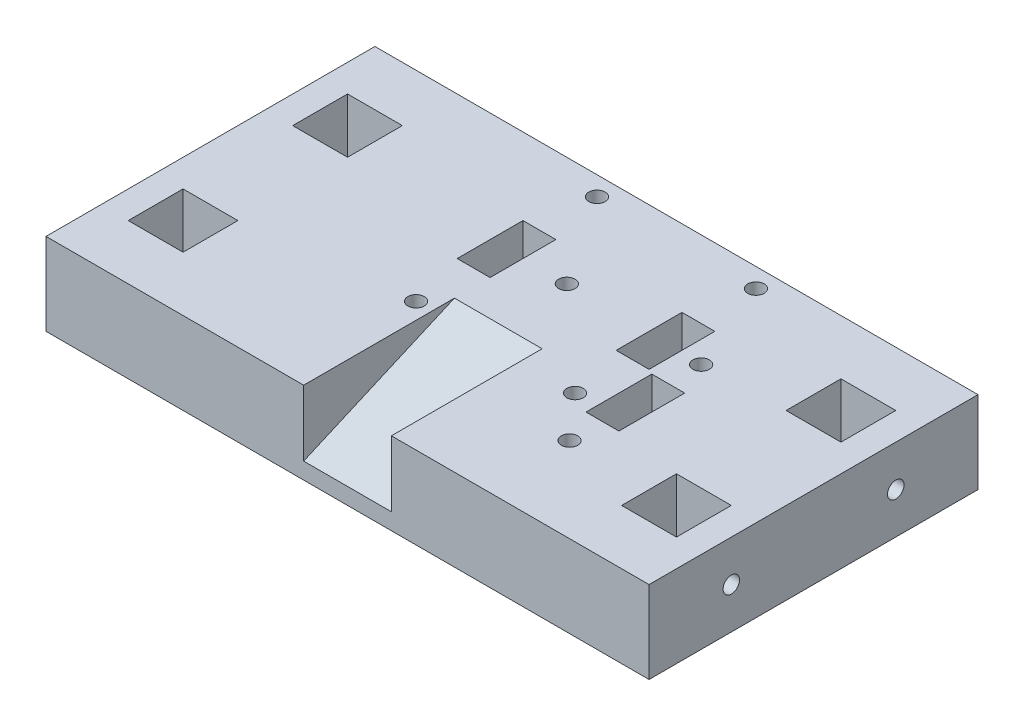
SolidWorks part; units mm, degrees
ref_plane "Alzado" through (0, 0, 0) normal (0, 0, 1) x (1, 0, 0)
ref_plane "Planta" through (0, 0, 0) normal (0, 1, 0) x (1, 0, 0)
ref_plane "Vista lateral" through (0, 0, 0) normal (1, 0, 0) x (0, 0, -1)
sketch "Croquis1" plane through (0, 0, 0) normal (0, 1, 0) x (1, 0, 0)
  line L0 (-50, 0) -> (55, 0) construction
  line L1 (0, 7.75) -> (-6.7117, 3.875)
  line L2 (-6.7117, 3.875) -> (-6.7117, -3.875)
  line L3 (-6.7117, -3.875) -> (0, -7.75)
  line L4 (0, -7.75) -> (6.7117, -3.875)
  line L5 (6.7117, -3.875) -> (6.7117, 3.875)
  line L6 (6.7117, 3.875) -> (0, 7.75)
  line L7 (-50, 20) -> (50, 20) construction
  line L8 (-50, -40) -> (50, -40) construction
  line L9 (-50, 10) -> (50, 10) construction
  line L10 (-50, 20) -> (-40, 20)
  line L11 (-50, 20) -> (-50, -40)
  line L12 (-50, -40) -> (-40, -40)
  line L13 (-40, 20) -> (-40, -40)
  line L14 (50, 20) -> (40, 20)
  line L15 (50, 20) -> (50, -40)
  line L16 (50, -40) -> (40, -40)
  line L17 (40, 20) -> (40, -40)
  line L18 (-40, 20) -> (40, 20)
  line L19 (-40, 20) -> (-40, -40)
  line L20 (-40, -40) -> (40, -40)
  line L21 (40, 20) -> (40, -40)
  line L22 (-50, -20) -> (50, -20) construction
  line L23 (-50, -30) -> (50, -30) construction
  line L24 (-14, 12.5) -> (21, 12.5) construction
  line L25 (-50, 10) -> (-40, 10)
  line L26 (-50, 10) -> (-50, 0)
  line L27 (-50, 0) -> (-40, 0)
  line L28 (-40, 10) -> (-40, 0)
  line L29 (50, 10) -> (40, 10)
  line L30 (50, 10) -> (50, 0)
  line L31 (50, 0) -> (40, 0)
  line L32 (40, 10) -> (40, 0)
  line L33 (50, -20) -> (40, -20)
  line L34 (50, -20) -> (50, -30)
  line L35 (50, -30) -> (40, -30)
  line L36 (40, -20) -> (40, -30)
  line L37 (-50, -20) -> (-40, -20)
  line L38 (-50, -20) -> (-50, -30)
  line L39 (-50, -30) -> (-40, -30)
  line L40 (-40, -20) -> (-40, -30)
  line L41 (-50, 20) -> (-55, 20)
  line L42 (-50, 20) -> (-50, -40)
  line L43 (-50, -40) -> (-55, -40)
  line L44 (-55, 20) -> (-55, -40)
  line L45 (50, 20) -> (55, 20)
  line L46 (50, 20) -> (50, -40)
  line L47 (50, -40) -> (55, -40)
  line L48 (55, 20) -> (55, -40)
  line L49 (-14, -12.5) -> (21, -12.5) construction
  line L50 (-11, 12.5) -> (-11, -12.5) construction
  line L51 (-14, 12.5) -> (-8, 12.5)
  line L52 (-14, 12.5) -> (-14, -12.5)
  line L53 (-14, -12.5) -> (-8, -12.5)
  line L54 (-8, 12.5) -> (-8, -12.5)
  line L55 (21, 12.5) -> (15, 12.5)
  line L56 (21, 12.5) -> (21, -12.5)
  line L57 (21, -12.5) -> (15, -12.5)
  line L58 (15, 12.5) -> (15, -12.5)
  line L59 (-14, 6) -> (-8, 6)
  line L60 (-14, 6) -> (-14, -6)
  line L61 (-14, -6) -> (-8, -6)
  line L62 (-8, 6) -> (-8, -6)
  line L63 (15, 6) -> (21, 6)
  line L64 (15, 6) -> (15, -6)
  line L65 (15, -6) -> (21, -6)
  line L66 (21, 6) -> (21, -6)
  line L67 (18, 12.5) -> (18, -12.5) construction
  circle A0 centre (0, 0) radius 7.75 construction
  circle A1 centre (-11, 16.5) radius 1.5
  circle A2 centre (18, 16.5) radius 1.5
  circle A3 centre (-11, -16.5) radius 1.5
  circle A4 centre (18, -16.5) radius 1.5
  dimension "D1" = 15.5
  dimension "D24" = 3
  dimension "D25" = 3
  dimension "D26" = 3
  dimension "D27" = 3
  dimension "D2" = 100
  dimension "D3" = 10
  dimension "D4" = 10
  dimension "D5" = 20
  dimension "D6" = 50
  dimension "D7" = 60
  dimension "D8" = 10
  dimension "D9" = 20
  dimension "D10" = 10
  dimension "D11" = 5
  dimension "D12" = 5
  dimension "D13" = 40
  dimension "D14" = 6
  dimension "D15" = 6
  dimension "D16" = 25
  dimension "D17" = 12.5
  dimension "D18" = 8
  dimension "D19" = 15
  dimension "D20" = 12
  dimension "D21" = 12
  dimension "D22" = 6.5
  dimension "D23" = 6.5
  dimension "D28" = 4
  dimension "D29" = 4
  dimension "D30" = 4
  dimension "D31" = 4
  dimension "D32" = 3
  dimension "D33" = 3
  dimension "D34" = 3
  dimension "D35" = 3
extrude "Saliente-Extruir1" add sketch "Croquis1" along normal blind 15 contours L13 L19 L20 L17 L21 L18 A4 A3 A2 A1 L58 L55 L56 L57 L6 L5 L4 L3 L2 L1 L51 L54 L53 L52 | L11 L37 L13 L27 | L39 L11 L12 L13 | L41 L44 L43 L11 | L11 L25 L13 L10 | L29 L15 L14 L17 | L48 L45 L15 L47 | L33 L15 L31 L17 | L15 L35 L17 L16 | L52 L59 L54 L51 | L61 L52 L53 L54 | L58 L63 L56 L55 | L65 L58 L57 L56
sketch "Croquis2" plane through (0, 0, 0) normal (0, -1, 0) x (1, 0, 0)
  line L1 (-7.3916, 16.5) -> (-9.1958, 19.625)
  line L2 (-9.1958, 19.625) -> (-12.8042, 19.625)
  line L3 (-12.8042, 19.625) -> (-14.6084, 16.5)
  line L4 (-14.6084, 16.5) -> (-12.8042, 13.375)
  line L5 (-12.8042, 13.375) -> (-9.1958, 13.375)
  line L6 (-9.1958, 13.375) -> (-7.3916, 16.5)
  line L7 (21.6084, 16.5) -> (19.8042, 19.625)
  line L8 (19.8042, 19.625) -> (16.1958, 19.625)
  line L9 (16.1958, 19.625) -> (14.3916, 16.5)
  line L10 (14.3916, 16.5) -> (16.1958, 13.375)
  line L11 (16.1958, 13.375) -> (19.8042, 13.375)
  line L12 (19.8042, 13.375) -> (21.6084, 16.5)
  line L13 (-7.3916, -16.5) -> (-9.1958, -13.375)
  line L14 (-9.1958, -13.375) -> (-12.8042, -13.375)
  line L15 (-12.8042, -13.375) -> (-14.6084, -16.5)
  line L16 (-14.6084, -16.5) -> (-12.8042, -19.625)
  line L17 (-12.8042, -19.625) -> (-9.1958, -19.625)
  line L18 (-9.1958, -19.625) -> (-7.3916, -16.5)
  line L19 (21.6084, -16.5) -> (19.8042, -13.375)
  line L20 (19.8042, -13.375) -> (16.1958, -13.375)
  line L21 (16.1958, -13.375) -> (14.3916, -16.5)
  line L22 (14.3916, -16.5) -> (16.1958, -19.625)
  line L23 (16.1958, -19.625) -> (19.8042, -19.625)
  line L24 (19.8042, -19.625) -> (21.6084, -16.5)
  circle A0 centre (-11, 16.5) radius 3.125 construction
  circle A1 centre (18, 16.5) radius 3.125 construction
  circle A2 centre (-11, -16.5) radius 3.125 construction
  circle A3 centre (18, -16.5) radius 3.125 construction
extrude "Cortar-Extruir1" cut sketch "Croquis2" against normal blind 10
sketch "Croquis3" plane through (55, 0, 0) normal (1, 0, 0) x (0, 0, -1)
  line L0 (-40, 7.5) -> (20, 7.5) construction
  line L1 (-40, 15) -> (-40, 0) construction
  line L2 (20, 15) -> (20, 0) construction
  circle A0 centre (-25, 7.5) radius 1.5
  circle A1 centre (5, 7.5) radius 1.5
  dimension "D3" = 3
  dimension "D4" = 3
  dimension "D1" = 15
  dimension "D2" = 15
extrude "Cortar-Extruir2" cut sketch "Croquis3" against normal blind 25
sketch "Croquis6" plane through (-55, 0, 0) normal (-1, 0, 0) x (0, 0, 1)
  line L0 (-20, 7.5) -> (40, 7.5) construction
  line L1 (-20, 15) -> (-20, 0) construction
  line L2 (40, 15) -> (40, 0) construction
  circle A0 centre (-5, 7.5) radius 1.5
  circle A1 centre (25, 7.5) radius 1.5
  dimension "D1" = 3
  dimension "D2" = 3
  dimension "D3" = 15
  dimension "D4" = 15
extrude "Cortar-Extruir3" cut sketch "Croquis6" against normal blind 25
sketch "Croquis8" plane through (0, 15, 0) normal (0, 1, 0) x (1, 0, 0)
  line L0 (-8, 6) -> (-8, -6) construction
  line L1 (8, -8.9241) -> (-8, -8.9241)
  line L2 (8, -8.9241) -> (8, 8.9241)
  line L3 (8, 8.9241) -> (-8, 8.9241)
  line L4 (-8, -8.9241) -> (-8, 8.9241)
  line L5 (8, -8.9241) -> (-8, 8.9241) construction
  line L6 (8, 8.9241) -> (-8, -8.9241) construction
  circle A0 centre (0, 0) radius 1.5
  point P0 (0, 0)
  dimension "D1" = 3
extrude "Saliente-Extruir2" add sketch "Croquis8" against normal blind 5
sketch "Croquis9" plane through (55, 0, 0) normal (1, 0, 0) x (0, 0, -1)
  line L0 (-12.5, 15) -> (-40, 3)
  line L1 (-40, 15) -> (0, 15)
  line L2 (-40, 15) -> (-40, 0)
  line L3 (-40, 0) -> (0, 0)
  line L4 (0, 15) -> (0, 0)
  circle M5 centre (-25, 7.5) radius 1.5
  line M7 (-40, 0) -> (20, 0)
  line M9 (20, 15) -> (-40, 15)
  line M10 (-40, 15) -> (-40, 0)
  dimension "D1" = 12.5
  dimension "D2" = 3
extrude "Cortar-Extruir4" cut sketch "Croquis9" against normal mid plane 16 from offset 55 contours L4 L0 M9 M10 M7 M5 offset against normal yes
sketch "Croquis10" plane through (0, 15, 0) normal (0, 1, 0) x (1, 0, 0)
  line L0 (25, 20) -> (25, -40) construction
  line L1 (-55, 20) -> (55, 20) construction
  line L2 (8, -40) -> (55, -40) construction
  line L4 (22, -18.5) -> (28, -18.5)
  line L5 (22, -18.5) -> (22, -6.5)
  line L6 (22, -6.5) -> (28, -6.5)
  line L7 (28, -18.5) -> (28, -6.5)
  line L8 (22, -18.5) -> (28, -6.5) construction
  line L9 (22, -6.5) -> (28, -18.5) construction
  circle A0 centre (25, -0.5) radius 1.5
  circle A1 centre (25, -24.5) radius 1.5
  point P6 (25, -12.5)
  dimension "D5" = 3
  dimension "D6" = 3
  dimension "D1" = 25
  dimension "D2" = 6
  dimension "D3" = 12
  dimension "D4" = 12.5
  dimension "D7" = 6
  dimension "D8" = 6
extrude "Cortar-Extruir5" cut sketch "Croquis10" against normal blind 16
sketch "Croquis11" plane through (0, 0, 0) normal (0, -1, 0) x (1, 0, 0)
  line L1 (28.6084, 24.5) -> (26.8042, 27.625)
  line L2 (26.8042, 27.625) -> (23.1958, 27.625)
  line L3 (23.1958, 27.625) -> (21.3916, 24.5)
  line L4 (21.3916, 24.5) -> (23.1958, 21.375)
  line L5 (23.1958, 21.375) -> (26.8042, 21.375)
  line L6 (26.8042, 21.375) -> (28.6084, 24.5)
  line L7 (28.6084, 0.5) -> (26.8042, 3.625)
  line L8 (26.8042, 3.625) -> (23.1958, 3.625)
  line L9 (23.1958, 3.625) -> (21.3916, 0.5)
  line L10 (21.3916, 0.5) -> (23.1958, -2.625)
  line L11 (23.1958, -2.625) -> (26.8042, -2.625)
  line L12 (26.8042, -2.625) -> (28.6084, 0.5)
  circle A0 centre (25, 24.5) radius 3.125 construction
  circle A1 centre (25, 0.5) radius 3.125 construction
extrude "Cortar-Extruir6" cut sketch "Croquis11" against normal blind 10
